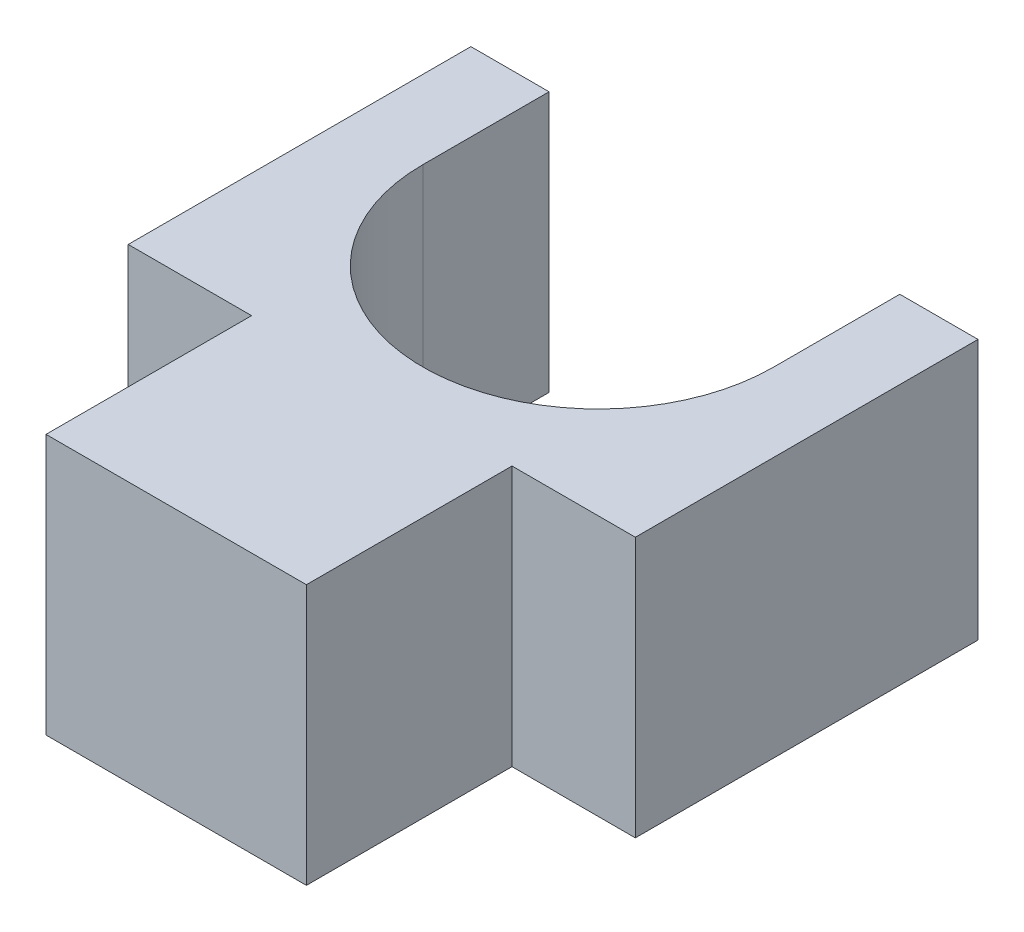
SolidWorks part; units mm, degrees
ref_plane "Front Plane" through (0, 0, 0) normal (0, 0, 1) x (1, 0, 0)
ref_plane "Top Plane" through (0, 0, 0) normal (0, 1, 0) x (1, 0, 0)
ref_plane "Right Plane" through (0, 0, 0) normal (1, 0, 0) x (0, 0, -1)
sketch "Sketch1" plane through (0, 0, 0) normal (0, 1, 0) x (1, 0, 0)
  line L0 (0, 0) -> (0, 11.2665) construction
  line L1 (1.2065, 0) -> (-1.2065, 0)
  line L2 (-1.2065, 0) -> (-1.2065, 1.905)
  line L3 (-1.625, 5.08) -> (-1.625, 3.911)
  line L4 (-1.2065, 1.905) -> (-2.3495, 1.905)
  line L5 (-2.3495, 1.905) -> (-2.3495, 5.08)
  line L6 (-2.3495, 5.08) -> (-1.625, 5.08)
  line L7 (2.3495, 5.08) -> (2.3495, 1.905)
  line L8 (1.2065, 0) -> (1.2065, 1.905)
  line L9 (2.3495, 1.905) -> (1.2065, 1.905)
  line L10 (0, 2.286) -> (0.5456, 2.286) construction
  line L11 (1.625, 3.911) -> (1.625, 5.08)
  line L12 (1.625, 5.08) -> (2.3495, 5.08)
  arc A0 (-1.625, 3.911) -> (1.625, 3.911) centre (0, 3.911) ccw
  dimension "D1" = 2.413
  dimension "5.12" = 1.905
  dimension "D2" = 4.699
  dimension "D3" = 3.175
  dimension "D4" = 3.25
  dimension "D5" = 2.794
extrude "Boss-Extrude1" add sketch "Sketch1" along normal blind 2.413
